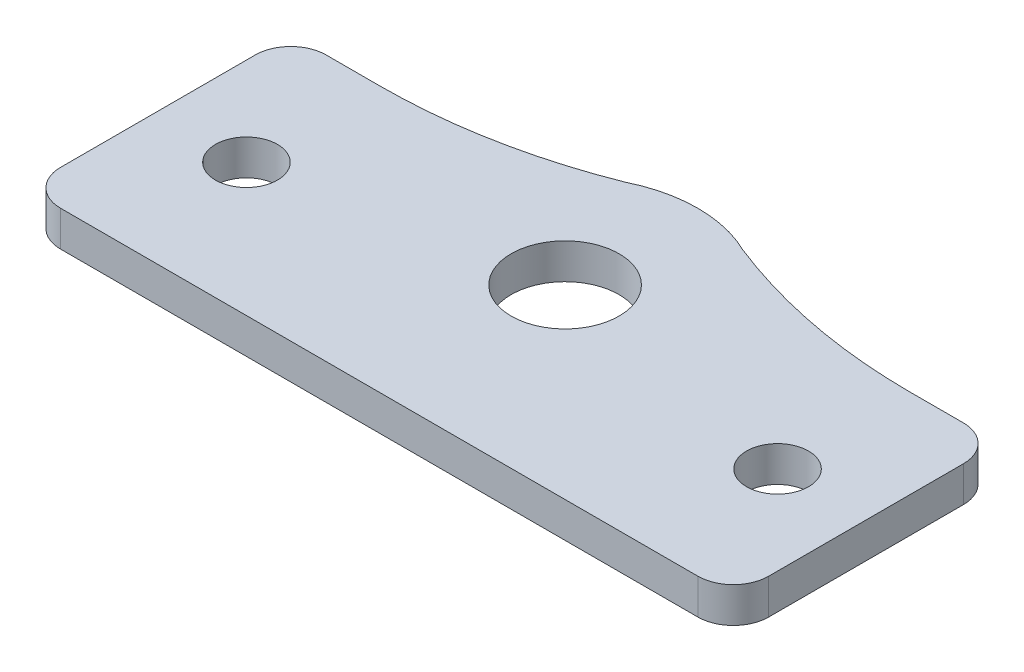
SolidWorks part; units mm, degrees
ref_plane "前视基准面" through (0, 0, 0) normal (0, 0, 1) x (1, 0, 0)
ref_plane "上视基准面" through (0, 0, 0) normal (0, 1, 0) x (1, 0, 0)
ref_plane "右视基准面" through (0, 0, 0) normal (1, 0, 0) x (0, 0, -1)
other "Configuration Table"
sketch "草图1" plane through (0, 0, 0) normal (0, 1, 0) x (1, 0, 0)
  line L0 (0, 0) -> (30, 0)
  line L1 (30, 0) -> (30, 15)
  line L3 (0, 15) -> (0, 0)
  line L4 (-16.6998, 7.5) -> (46.9688, 7.5) construction
  line L5 (15, 26.0996) -> (15, -11.7011) construction
  line L6 (0, 15) -> (-3, 15)
  line L7 (-5, 13) -> (-5, 2)
  line L8 (-3, 0) -> (0, 0)
  line L9 (-3, 15) -> (0, 15)
  line L10 (33, 15) -> (30, 15)
  line L11 (33, 0) -> (30, 0)
  line L12 (35, 13) -> (35, 2)
  line L13 (30, 15) -> (33, 15)
  circle A0 centre (15, 10.5) radius 3.05
  arc A1 (8.1261, 7.5) -> (15, 3) centre (15, 10.5) ccw
  arc A2 (0, 15) -> (11.701, 17.2355) centre (0, 46.7407) ccw
  arc A3 (30, 15) -> (18.299, 17.2355) centre (30, 46.7407) cw
  arc A4 (-3, 0) -> (-5, 2) centre (-3, 2) cw
  arc A5 (-5, 13) -> (-3, 15) centre (-3, 13) cw
  circle A6 centre (0, 7.5) radius 1.75
  circle A7 centre (30, 7.5) radius 1.75
  arc A8 (35, 13) -> (33, 15) centre (33, 13) ccw
  arc A9 (33, 0) -> (35, 2) centre (33, 2) ccw
  arc A10 (18.299, 17.2355) -> (11.701, 17.2355) centre (15, 10.5) ccw
  point P20 (-5, 0)
  point P33 (35, 0)
  dimension "D1" = 6.1
  dimension "D4" = 15
  dimension "D7" = 2
  dimension "D8" = 3.5
  dimension "D2" = 15
  dimension "D3" = 3
  dimension "D5" = 30
  dimension "D6" = 5
extrude "凸台-拉伸1" add sketch "草图1" along normal blind 2
